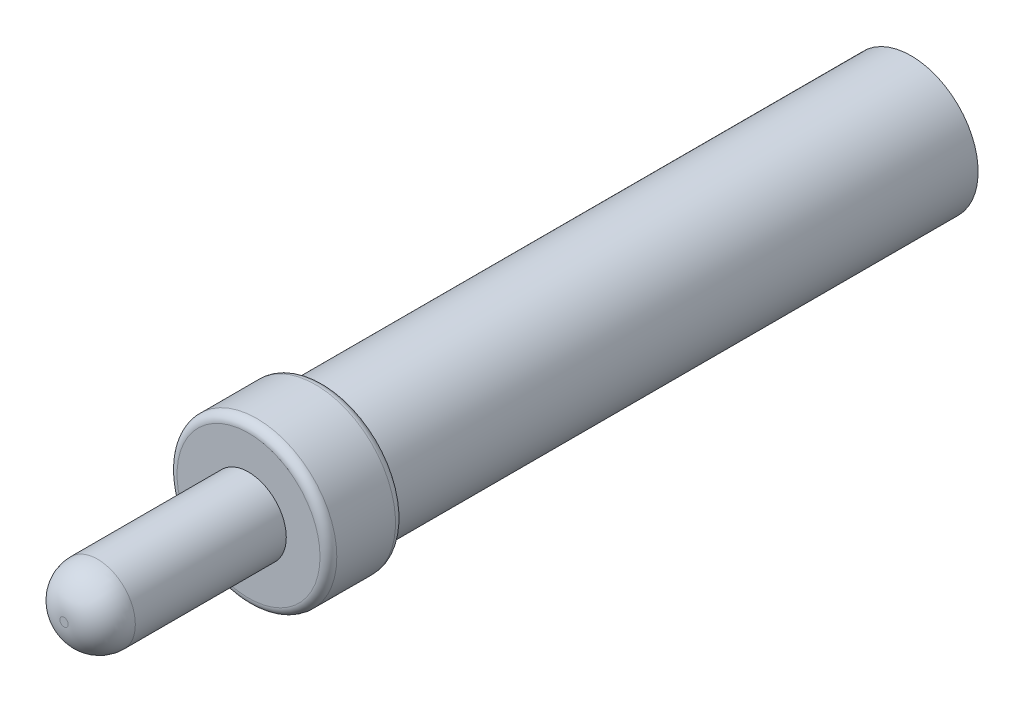
SolidWorks part; units mm, degrees
ref_plane "Plano frontal" through (0, 0, 0) normal (0, 0, 1) x (1, 0, 0)
ref_plane "Plano superior" through (0, 0, 0) normal (0, 1, 0) x (1, 0, 0)
ref_plane "Plano direito" through (0, 0, 0) normal (1, 0, 0) x (0, 0, -1)
sketch "Esboço1" plane through (0, 0, 0) normal (0, 0, 1) x (1, 0, 0)
  circle A0 centre (240.7084, 2.5961) radius 4.7625
  dimension "D1" = 9.525
extrude "Ressalto-extrusão1" add sketch "Esboço1" along normal blind 50.5
hole_wizard "Furo roscado de M3x0.52" positions "Esboço5" profile "Esboço4" tap size "M3x0.5" standard "Métrico Ansi"
sketch "Esboço5" plane through (0, 0, 0) normal (0, 0, -1) x (-1, 0, 0)
  point P0 (-240.7084, 2.5961)
sketch "Esboço4" plane through (240.7084, 2.5961, 0) normal (1, 0, 0) x (0, 1, 0)
  line L0 (0, 0) -> (0, 9.2511)
  line L1 (0, 9.2511) -> (1.25, 8.5)
  line L2 (1.25, 8.5) -> (1.25, 0)
  line L5 (1.25, 0) -> (0, 0)
  line L10 (0, 9.2511) -> (-1.25, 8.5) construction
  line L11 (0, -6.35) -> (0, 107.95) construction
  dimension "Tap Drill Dia." = 2.5
  dimension "Tap Drill Depth" = 8.5
  dimension "Drill Angle" = 118
cosmetic thread "Rosca de furo2" parameters "D1"=6, "D2"=3
cosmetic thread "Representação de rosca1" parameters "D1"=6, "D2"=3
sketch "Esboço8" plane through (0, 0, 0) normal (0, 0, -1) x (-1, 0, 0)
  circle A0 centre (-240.7084, 2.5961) radius 4
  dimension "D1" = 8
extrude "Corte-extrusão1" cut sketch "Esboço8" against normal blind 35 flip side to cut
sketch "Esboço10" plane through (0, 0, 50.5) normal (0, 0, 1) x (1, 0, 0)
  circle A0 centre (240.7084, 2.5961) radius 2.25
  dimension "D1" = 4.5
extrude "Corte-extrusão2" cut sketch "Esboço10" against normal blind 11 flip side to cut
fillet "Filete1" radius 0.5 2 edges at (235.9459, 2.5961, 35) (245.4709, 2.5961, 39.5)
fillet "Filete2" radius 2 1 edges at (242.9584, 2.5961, 50.5)
